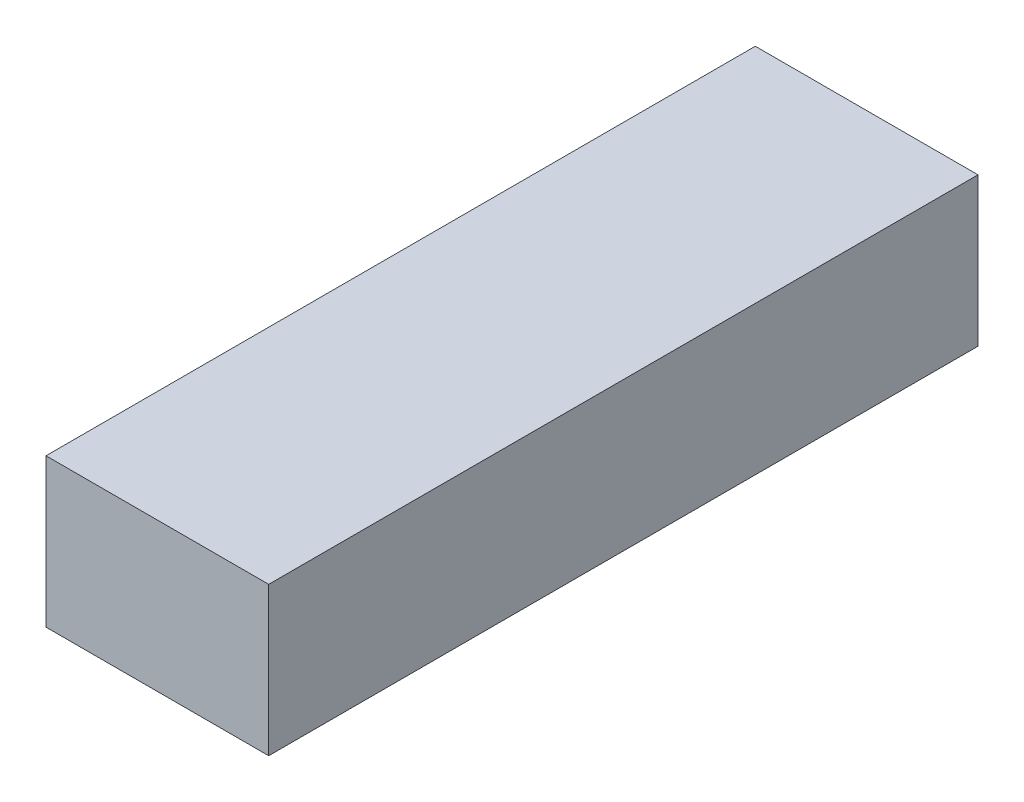
SolidWorks part; units mm, degrees
ref_plane "Front Plane" through (0, 0, 0) normal (0, 0, 1) x (1, 0, 0)
ref_plane "Top Plane" through (0, 0, 0) normal (0, 1, 0) x (1, 0, 0)
ref_plane "Right Plane" through (0, 0, 0) normal (1, 0, 0) x (0, 0, -1)
sketch "Sketch1" plane through (0, 0, 0) normal (0, 0, 1) x (1, 0, 0)
  line L1 (-21.4312, -14.2875) -> (21.4313, -14.2875)
  line L2 (-21.4312, -14.2875) -> (-21.4312, 14.2875)
  line L3 (-21.4312, 14.2875) -> (21.4313, 14.2875)
  line L4 (21.4313, -14.2875) -> (21.4313, 14.2875)
  line L5 (-21.4312, -14.2875) -> (21.4313, 14.2875) construction
  line L6 (-21.4312, 14.2875) -> (21.4313, -14.2875) construction
  point P0 (0, 0)
  dimension "D1" = 42.8625
  dimension "D2" = 28.575
extrude "Boss-Extrude1" add sketch "Sketch1" along normal mid plane 136.525
